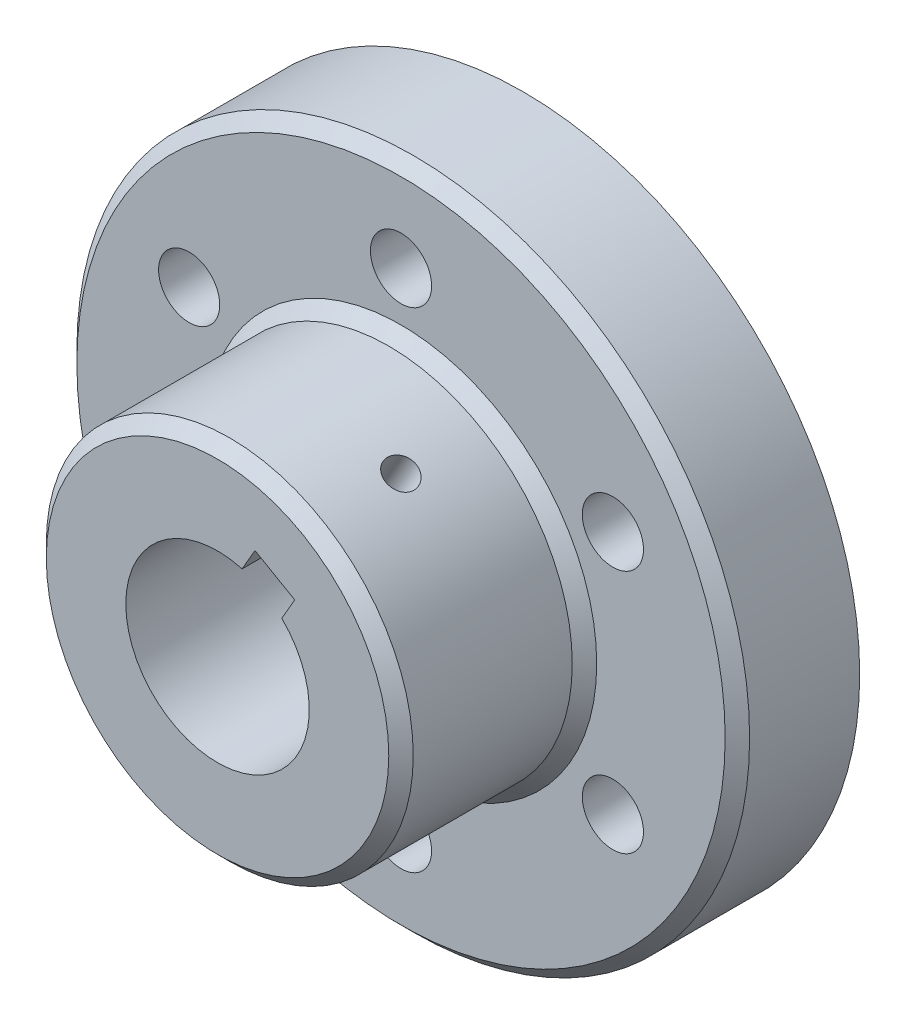
SolidWorks part; units mm, degrees
material "6061 Alloy"
ref_plane "Front Plane" through (0, 0, 0) normal (0, 0, 1) x (1, 0, 0)
ref_plane "Top Plane" through (0, 0, 0) normal (0, 1, 0) x (1, 0, 0)
ref_plane "Right Plane" through (0, 0, 0) normal (1, 0, 0) x (0, 0, -1)
sketch "Sketch1" plane through (0, 0, 0) normal (0, 0, 1) x (1, 0, 0)
  circle A0 centre (0, 0) radius 34.925
  dimension "D1" = 69.85
extrude "Extrude1" add sketch "Sketch1" along normal blind 12.7
sketch "Sketch2" plane through (0, 0, 12.7) normal (0, 0, 1) x (1, 0, 0)
  circle A0 centre (0, 0) radius 19.05
  dimension "D1" = 38.1
extrude "Extrude2" add sketch "Sketch2" along normal blind 19.05
sketch "Sketch3" plane through (0, 0, 0) normal (0, 0, -1) x (-1, 0, 0)
  circle A0 centre (0, 25.4) radius 3.175
  circle A1 centre (0, 0) radius 9.525
  dimension "D1" = 6.35
  dimension "D3" = 19.05
  dimension "D2" = 25.4
extrude "Cut-Extrude1" cut sketch "Sketch3" against normal through all
pattern_circular "CirPattern1" count 6 over 360 about axis through (0, 0, 0) along (0, 0, 1) of "Cut-Extrude1"
sketch "Sketch4" plane through (0, 0, 0) normal (0, 0, -1) x (-1, 0, 0)
  line L0 (0, 0) -> (-18.5212, 0) construction
  line L1 (-1.5097, 7.3773) -> (-5.6341, 4.996)
  line L2 (-1.5097, 7.3773) -> (-3.8909, 11.5017)
  line L3 (-3.8909, 11.5017) -> (-8.0153, 9.1205)
  line L4 (-5.6341, 4.996) -> (-8.0153, 9.1205)
  line L5 (-5.9531, 10.3111) -> (0, 0) construction
  point P4 (-5.9531, 10.3111)
  point P8 (-3.5719, 6.1867)
  dimension "D1" = 4.7625
  dimension "D2" = 4.7625
  dimension "D3" = 7.1437
  dimension "D4" = 60
extrude "Cut-Extrude2" cut sketch "Sketch4" against normal through all
sketch "Sketch5" plane through (5.9531, 10.3111, 0) normal (-0.5, -0.866, 0) x (0.866, -0.5, 0)
  line L0 (0, 31.75) -> (0, 12.7) construction
  line L1 (-2.3812, 31.75) -> (2.3813, 31.75) construction
  circle A0 centre (0, 22.225) radius 1.5875
  dimension "D1" = 3.175
  dimension "D2" = 9.525
extrude "Cut-Extrude3" cut sketch "Sketch5" against normal through all
chamfer "Chamfer1" distance 1.27 angle 45 3 edges at (19.05, 0, 12.7) (19.05, 0, 31.75) (34.925, 0, 12.7)
